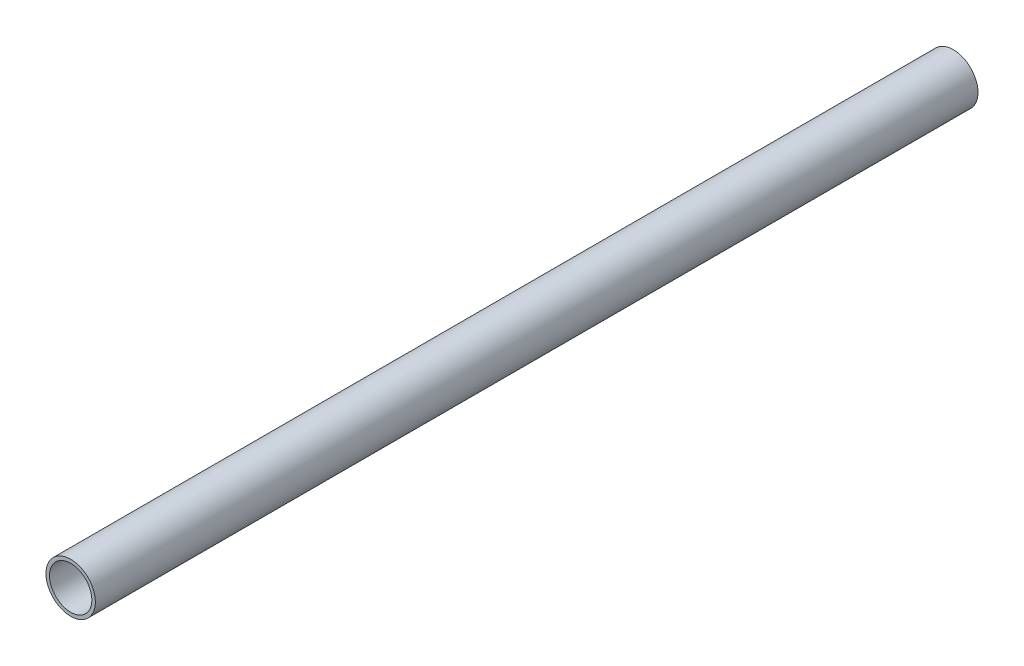
SolidWorks part; units mm, degrees
ref_plane "Piano frontale" through (0, 0, 0) normal (0, 0, 1) x (1, 0, 0)
ref_plane "Piano superiore" through (0, 0, 0) normal (0, 1, 0) x (1, 0, 0)
ref_plane "Piano destro" through (0, 0, 0) normal (1, 0, 0) x (0, 0, -1)
sketch "Schizzo1" plane through (0, 0, 0) normal (0, 0, 1) x (1, 0, 0)
  circle A0 centre (-2.3712, 4.2887) radius 7
  circle A1 centre (-2.3712, 4.2887) radius 6
  dimension "D1" = 1
  dimension "D2" = 14
extrude "Estrusione-Estrusione1" add sketch "Schizzo1" along normal blind 250
